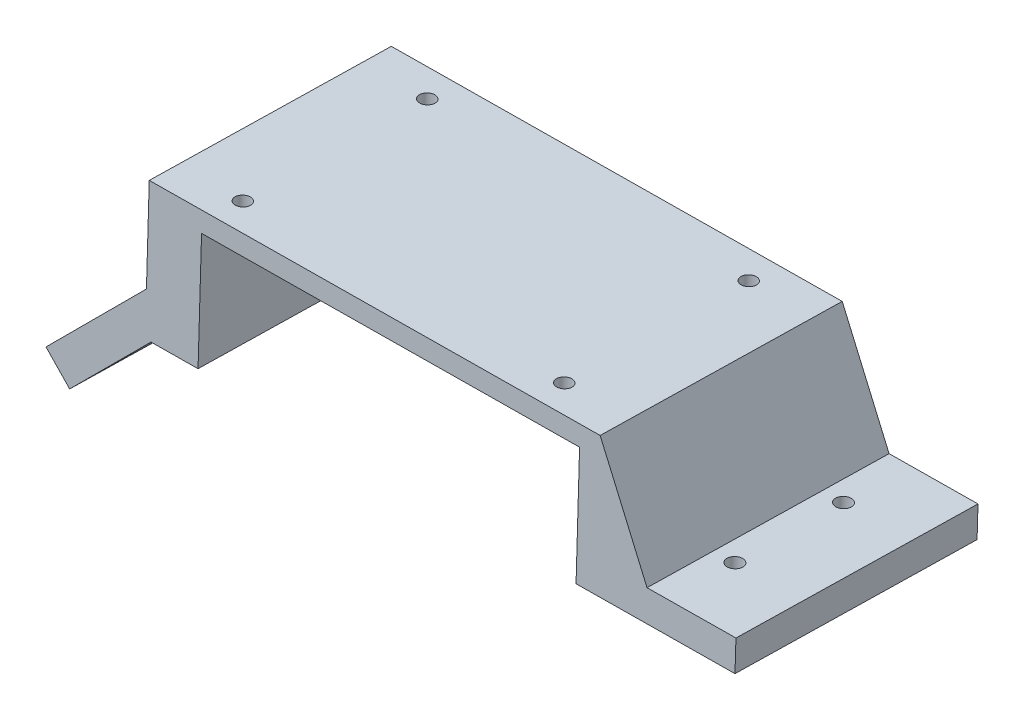
SolidWorks part; units mm, degrees
ref_plane "Front Plane" through (0, 0, 0) normal (0, 0, 1) x (1, 0, 0)
ref_plane "Top Plane" through (0, 0, 0) normal (0, 1, 0) x (1, 0, 0)
ref_plane "Right Plane" through (0, 0, 0) normal (1, 0, 0) x (0, 0, -1)
sketch "Sketch1" plane through (0, 0, 0) normal (0, 1, 0) x (1, 0, 0)
  point P0 (0, 0)
sketch "Sketch3" plane through (0.3986, 1.1741, 38.4253) normal (0.0104, 0.0305, 0.9995) x (0.9999, -0.0002, -0.0104)
  line L27 (35.8117, 184.6865) -> (70.1017, 184.6865)
  line L30 (-45.7368, 184.9117) -> (-55.8968, 184.9117)
  line L33 (-45.7368, 184.9117) -> (-45.7368, 210.0865)
  line L34 (-45.7368, 210.0865) -> (35.8117, 210.0865)
  line L35 (35.8117, 210.0865) -> (35.8117, 184.6865)
  line L38 (40.1193, 214.3723) -> (-57.15, 214.3723)
  line L40 (70.1017, 184.6865) -> (70.1017, 191.3258)
  line L41 (70.1017, 191.3258) -> (50.924, 191.3258)
  line L42 (50.924, 191.3258) -> (40.1193, 214.3723)
  line L43 (-55.8968, 184.9117) -> (-72.9257, 167.8828)
  line L44 (-72.9257, 167.8828) -> (-78.1834, 173.1405)
  line L45 (-78.1834, 173.1405) -> (-57.15, 194.174)
  line L46 (-57.15, 194.174) -> (-57.15, 214.3723)
  dimension "D1" = 10.16
  dimension "D2" = 34.29
extrude "Boss-Extrude2" add sketch "Sketch3" against normal blind 53.34
sketch "Sketch4" plane through (-0.0303, 191.2365, -5.8432) normal (-0.0002, 0.9995, -0.0305) x (1, 0.0002, 0)
  line L0 (70.4965, -37.7165) -> (50.7668, 15.4219) construction
  line L1 (60.6316, -11.1473) -> (60.9081, -37.8159) construction
  line L2 (70.4965, -37.7165) -> (51.3198, -37.9153) construction
  line L3 (60.6316, -11.1473) -> (51.0433, -11.2467) construction
  line L4 (50.7668, 15.4219) -> (51.3198, -37.9153) construction
  circle A0 centre (55.7187, -23.1656) radius 1.7
  circle A1 centre (55.4706, 0.7665) radius 1.7
  dimension "D1" = 3.4
extrude "Cut-Extrude1" cut sketch "Sketch4" against normal through all
sketch "Sketch5" plane through (-125.6751, 125.6233, -2.535) normal (-0.7072, 0.7069, -0.0143) x (-0.0101, 0.0101, 0.9999)
  line L0 (-17.6914, 96.4191) -> (36.4868, 68.2289) construction
  line L1 (9.8279, 76.9668) -> (9.8279, 67.4573) construction
  line L2 (-16.8309, 66.6858) -> (36.4868, 68.2289) construction
  circle A0 centre (27.3533, 72.7605) radius 1.65
  circle A1 centre (17.4312, 84.0182) radius 1.65
  circle A2 centre (2.2247, 84.0182) radius 1.65
  circle A3 centre (-7.6974, 72.7605) radius 1.65
  dimension "D1" = 3.3
extrude "Cut-Extrude2" cut sketch "Sketch5" against normal through all
sketch "Sketch6" plane through (-0.0339, 214.2723, -6.547) normal (-0.0002, 0.9995, -0.0305) x (1, 0.0002, 0)
  circle A0 centre (-43.2663, 8.0966) radius 1.6555
  circle A1 centre (26.072, 8.8155) radius 1.651
  circle A2 centre (26.4933, -31.8223) radius 1.651
  circle A3 centre (-42.8449, -32.5412) radius 1.651
extrude "Cut-Extrude3" cut sketch "Sketch6" against normal up to next
